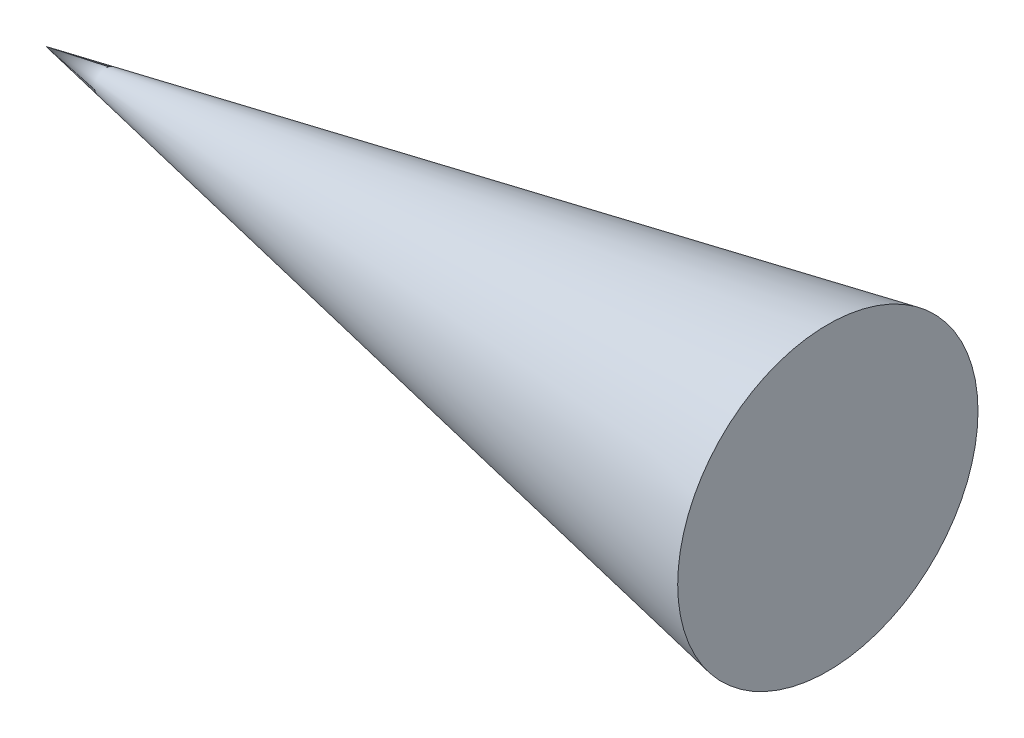
SolidWorks part; units mm, degrees
ref_plane "前视基准面" through (0, 0, 0) normal (0, 0, 1) x (1, 0, 0)
ref_plane "上视基准面" through (0, 0, 0) normal (0, 1, 0) x (1, 0, 0)
ref_plane "右视基准面" through (0, 0, 0) normal (1, 0, 0) x (0, 0, -1)
other "Configuration Table"
sketch "草图1" plane through (0, 0, 0) normal (0, 0, 1) x (1, 0, 0)
  line L0 (0, 0) -> (88.7257, 0)
  line L1 (88.7257, 0) -> (88.7257, 17.0403)
  line L2 (88.7257, 17.0403) -> (0, 0)
  point P3 (88.7257, 0)
revolve "旋转1" add sketch "草图1" angle 360 about L0
